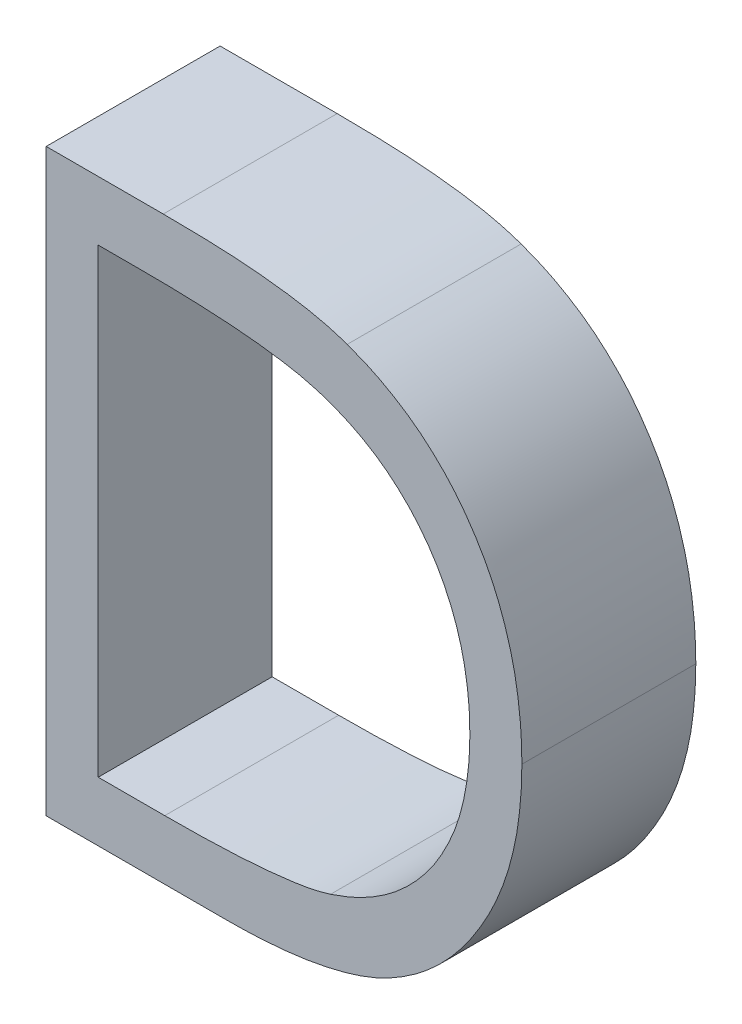
SolidWorks part; units mm, degrees
ref_plane "Plan de face" through (0, 0, 0) normal (0, 0, 1) x (1, 0, 0)
ref_plane "Plan de dessus" through (0, 0, 0) normal (0, 1, 0) x (1, 0, 0)
ref_plane "Plan de droite" through (0, 0, 0) normal (1, 0, 0) x (0, 0, -1)
sketch "Esquisse1" plane through (0, 0, 0) normal (0, 0, 1) x (1, 0, 0)
  text T0 "D" font "Century Gothic" height 5
extrude "Boss.-Extru.1" add sketch "Esquisse1" along normal blind 1.5
